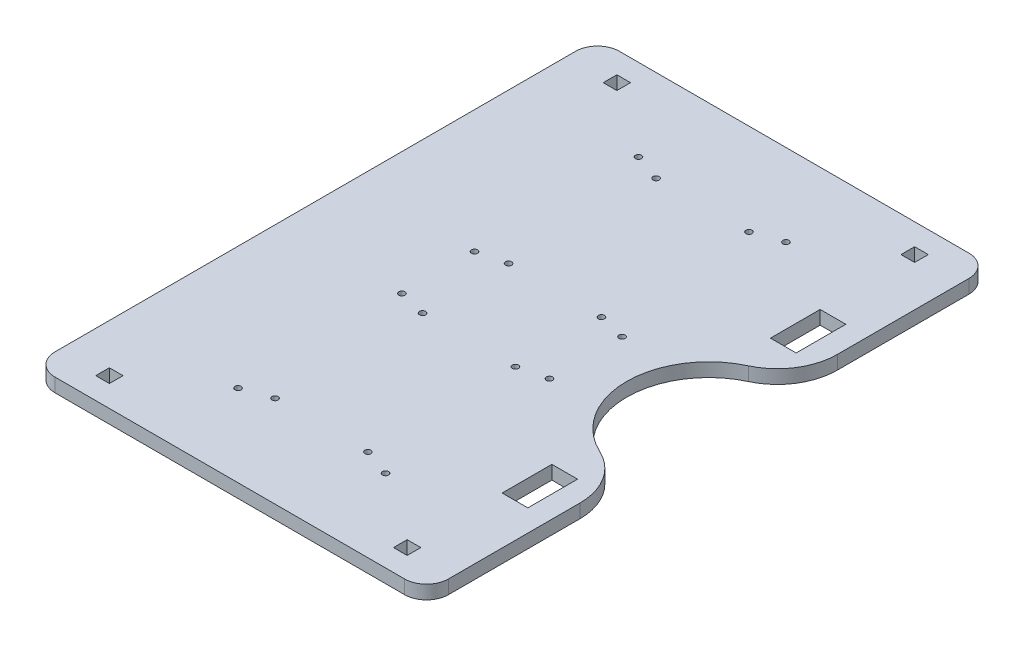
SolidWorks part; units mm, degrees
ref_plane "Front Plane" through (0, 0, 0) normal (0, 0, 1) x (1, 0, 0)
ref_plane "Top Plane" through (0, 0, 0) normal (0, 1, 0) x (1, 0, 0)
ref_plane "Right Plane" through (0, 0, 0) normal (1, 0, 0) x (0, 0, -1)
sketch "Sketch3" plane through (0, 0, 0) normal (0, 1, 0) x (1, 0, 0)
  line L4 (182.88, 0) -> (0, 0)
  line L5 (91.44, 262.3393) -> (91.44, 0) construction
  line L6 (19.05, 16.3877) -> (25.4, 16.3877)
  line L7 (19.05, 16.3877) -> (19.05, 10.0377)
  line L8 (19.05, 10.0377) -> (25.4, 10.0377)
  line L9 (25.4, 16.3877) -> (25.4, 10.0377)
  line L10 (163.83, 10.0377) -> (157.48, 10.0377)
  line L11 (157.48, 16.3877) -> (157.48, 10.0377)
  line L12 (163.83, 16.3877) -> (157.48, 16.3877)
  line L13 (163.83, 16.3877) -> (163.83, 10.0377)
  line L14 (0, 0) -> (0, 262.3393)
  line L15 (0, 262.3393) -> (182.88, 262.3393)
  line L16 (182.88, 262.3393) -> (182.88, 169.2696)
  line L17 (0, 131.1696) -> (152.4, 131.1696) construction
  line L18 (163.83, 245.9515) -> (163.83, 252.3015)
  line L19 (163.83, 245.9515) -> (157.48, 245.9515)
  line L20 (157.48, 245.9515) -> (157.48, 252.3015)
  line L21 (163.83, 252.3015) -> (157.48, 252.3015)
  line L22 (19.05, 252.3015) -> (25.4, 252.3015)
  line L23 (25.4, 245.9515) -> (25.4, 252.3015)
  line L24 (19.05, 245.9515) -> (25.4, 245.9515)
  line L25 (19.05, 245.9515) -> (19.05, 252.3015)
  line L26 (182.88, 93.0696) -> (182.88, 0)
  line L27 (172.72, 205.0836) -> (160.782, 205.0836)
  line L28 (172.72, 80.3696) -> (160.782, 80.3696)
  line L29 (172.72, 80.3696) -> (172.72, 57.2556)
  line L30 (172.72, 57.2556) -> (160.782, 57.2556)
  line L31 (160.782, 80.3696) -> (160.782, 57.2556)
  line L32 (172.72, 181.9696) -> (160.782, 181.9696)
  line L33 (172.72, 181.9696) -> (172.72, 205.0836)
  line L34 (160.782, 181.9696) -> (160.782, 205.0836)
  circle A6 centre (57.15, 38.1) radius 1.4224
  circle A7 centre (57.15, 114.3) radius 1.4224
  circle A8 centre (125.73, 114.3) radius 1.4224
  circle A9 centre (125.73, 38.1) radius 1.4224
  circle A10 centre (69.85, 151.1577) radius 1.4224
  circle A11 centre (69.85, 219.7377) radius 1.4224
  circle A12 centre (113.03, 151.1577) radius 1.4224
  circle A13 centre (113.03, 219.7377) radius 1.4224
  circle A14 centre (113.03, 42.6016) radius 1.4224
  circle A15 centre (113.03, 111.1816) radius 1.4224
  circle A16 centre (69.85, 111.1816) radius 1.4224
  circle A17 centre (69.85, 42.6016) radius 1.4224
  circle A18 centre (125.73, 148.0393) radius 1.4224
  circle A19 centre (125.73, 224.2393) radius 1.4224
  circle A20 centre (57.15, 224.2393) radius 1.4224
  circle A21 centre (57.15, 148.0393) radius 1.4224
  arc A22 (182.88, 169.2696) -> (182.88, 93.0696) centre (182.88, 131.1696) ccw
  dimension "D2" = 19.05
  dimension "D3" = 0
  dimension "D10" = 38.1
  dimension "D13" = 68.58
  dimension "D8" = 23.114
  dimension "D4" = 19.05
  dimension "D5" = 182.88
  dimension "D6" = 6.35
  dimension "D7" = 6.35
  dimension "D9" = 11.938
  dimension "D11" = 76.2
  dimension "D12" = 68.58
  dimension "D14" = 43.18
  dimension "D15" = 50.8
  dimension "D16" = 10.16
extrude "Boss-Extrude1" add sketch "Sketch3" along normal blind 6.35
fillet "Fillet1" radius 10.16 4 edges at (0, 3.175, 0) (0, 3.175, -262.3393) (182.88, 3.175, -262.3393) (182.88, 3.175, 0)
fillet "Fillet2" radius 27.94 2 edges at (182.88, 3.175, -169.2696) (182.88, 3.175, -93.0696)
